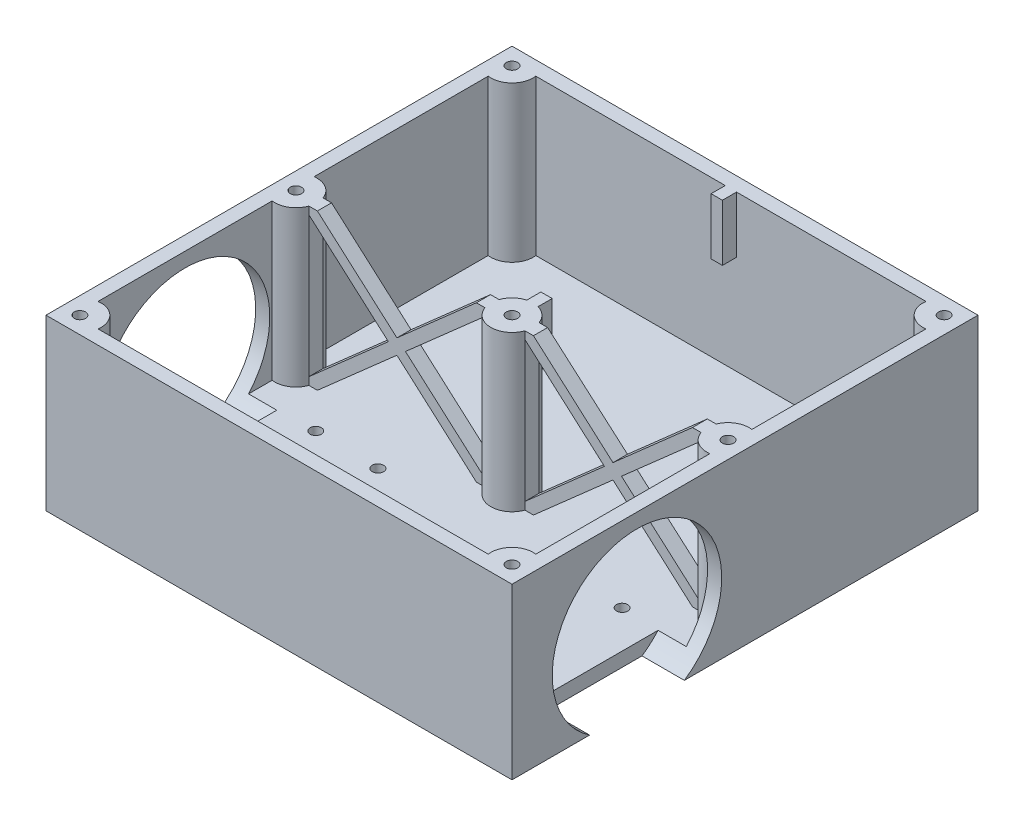
SolidWorks part; units mm, degrees
ref_plane "Plan de face" through (0, 0, 0) normal (0, 0, 1) x (1, 0, 0)
ref_plane "Plan de dessus" through (0, 0, 0) normal (0, 1, 0) x (1, 0, 0)
ref_plane "Plan de droite" through (0, 0, 0) normal (1, 0, 0) x (0, 0, -1)
sketch "Esquisse1" plane through (0, 0, 0) normal (0, 1, 0) x (1, 0, 0)
  line L0 (0, -92.04) -> (0, 96.9003) construction
  line L1 (82.5, 82.5) -> (-82.5, 82.5)
  line L2 (82.5, 82.5) -> (82.5, -82.5)
  line L3 (82.5, -82.5) -> (-82.5, -82.5)
  line L4 (-82.5, 82.5) -> (-82.5, -82.5)
  line L5 (82.5, 82.5) -> (-82.5, -82.5) construction
  line L6 (82.5, -82.5) -> (-82.5, 82.5) construction
  line L7 (69.067, -77.5) -> (-69.067, -77.5)
  line L8 (77.5, -69.067) -> (77.5, -7.433)
  line L9 (69.067, 77.5) -> (2, 77.5)
  line L10 (-77.5, -69.067) -> (-77.5, -7.433)
  line L11 (76.5, -76.5) -> (-76.5, 76.5) construction
  line L12 (76.5, 76.5) -> (-76.5, -76.5) construction
  line L13 (0, 0) -> (-103.5856, 0) construction
  line L14 (-77.5, 7.433) -> (-77.5, 69.067)
  line L15 (77.5, 7.433) -> (77.5, 69.067)
  line L16 (-69.4289, 2.5) -> (-7.0711, 2.5)
  line L17 (-69.4289, -2.5) -> (-7.0711, -2.5)
  line L18 (-2, 77.5) -> (-2, 7.2284)
  line L19 (7.0711, 2.5) -> (69.5275, 2.763)
  line L20 (7.0711, -2.5) -> (69.4289, -2.5)
  line L21 (2, 77.5) -> (2, 7.2284)
  line L22 (-2, 77.5) -> (-69.067, 77.5)
  line L23 (-76.5, -76.5) -> (-76.5, 76.5) construction
  arc A0 (-77.5, 69.067) -> (-69.067, 77.5) centre (-76.5, 76.5) ccw
  circle A1 centre (-76.5, 76.5) radius 2
  arc A2 (-77.5, -7.433) -> (-77.5, 7.433) centre (-76.5, 0) ccw
  circle A3 centre (-76.5, 0) radius 2
  circle A4 centre (-76.5, -76.5) radius 2
  arc A5 (-77.5, -69.067) -> (-69.067, -77.5) centre (-76.5, -76.5) cw
  circle A6 centre (76.5, 76.5) radius 2
  arc A7 (77.5, 69.067) -> (69.067, 77.5) centre (76.5, 76.5) cw
  arc A8 (77.5, -7.433) -> (77.5, 7.433) centre (76.5, 0) cw
  circle A9 centre (76.5, 0) radius 2
  circle A10 centre (76.5, -76.5) radius 2
  arc A11 (77.5, -69.067) -> (69.067, -77.5) centre (76.5, -76.5) ccw
  arc A12 (7.0711, 2.5) -> (2, 7.2284) centre (0, 0) ccw
  circle A13 centre (0, 0) radius 2
  arc A14 (-7.0711, -2.5) -> (7.0711, -2.5) centre (0, 0) ccw
  arc A15 (-2, 7.2284) -> (-7.0711, 2.5) centre (0, 0) ccw
  point P0 (0, 0)
  point P6 (0, 0)
  dimension "D3" = 15
  dimension "D6" = 4
  dimension "D8" = 4
  dimension "D9" = 2.5
  dimension "D10" = 15
  dimension "D11" = 4
  dimension "D15" = 7.5
  dimension "D1" = 165
  dimension "D2" = 165
  dimension "D4" = 5
  dimension "D5" = 5
  dimension "D7" = 2.5
  dimension "D12" = 2
  dimension "D13" = 2
  dimension "D14" = 6
extrude "BASE EXT" add sketch "Esquisse1" along normal blind 30 and the other way blind 25
sketch "Esquisse2" plane through (0, -25, 0) normal (0, -1, 0) x (1, 0, 0)
  line L0 (0, 93.4226) -> (0, -99.355) construction
  line L1 (82.5, 82.5) -> (-82.5, 82.5)
  line L2 (82.5, 82.5) -> (82.5, -82.5)
  line L3 (82.5, -82.5) -> (-82.5, -82.5)
  line L4 (-82.5, 82.5) -> (-82.5, -82.5)
  line L5 (82.5, 82.5) -> (-82.5, -82.5) construction
  line L6 (82.5, -82.5) -> (-82.5, 82.5) construction
  circle A35 centre (-76.5, 0) radius 5
  circle A36 centre (-76.5, -76.5) radius 5
  circle A37 centre (76.5, -76.5) radius 5
  circle A38 centre (76.5, 0) radius 5
  circle A39 centre (76.5, 76.5) radius 5
  circle A40 centre (0, 0) radius 5
  circle A42 centre (-76.5, 76.5) radius 5
  point P0 (0, 0)
  dimension "D1" = 10
  dimension "D2" = 10
  dimension "D3" = 10
  dimension "D4" = 10
extrude "BASE BAS" add sketch "Esquisse2" along normal blind 5
sketch "Esquisse4" plane through (-77.5, 0, 0) normal (1, 0, 0) x (0, 0, -1)
  line L1 (-69.067, -25) -> (-7.433, -25) construction
  line L2 (-38.25, -25) -> (-38.25, 16.399) construction
  circle A0 centre (-38.25, -5.1286) radius 30
  point P0 (-38.25, -25)
  point P7 (-38.25, 24.8714)
  dimension "D1" = 60
extrude "ACCES ROUES" cut sketch "Esquisse4" against normal blind 6 and the other way blind 10
mirror "SYM ACCES ROUE" about plane through (0, 0, 0) normal (1, 0, 0) of "ACCES ROUES"
sketch "Esquisse7" plane through (0, -25, 0) normal (0, 1, 0) x (1, 0, 0)
  line L0 (-54.2324, -15.25) -> (-54.2324, -61.25) construction
  line L1 (-54.2324, -61.25) -> (-31.7324, -60.75) construction
  line L2 (-31.7324, -60.75) -> (-31.7324, -15.75) construction
  line L3 (-31.7324, -15.75) -> (-54.2324, -15.25) construction
  line L4 (-54.2324, -15.25) -> (-31.7324, -60.75) construction
  line L5 (-31.7324, -60.75) -> (-54.2324, -61.25) construction
  line L6 (-54.2324, -61.25) -> (-31.7324, -15.75) construction
  line L7 (0, 0) -> (-76.5, -76.5) construction
  line L8 (-38.25, -38.25) -> (-73.5574, -38.25) construction
  line L9 (-42.8587, -38.25) -> (-69.3083, -38.25) construction
  line L10 (0, 0) -> (0, -89.1386) construction
  line L11 (54.2324, -61.25) -> (31.7324, -15.75) construction
  line L12 (31.7324, -60.75) -> (54.2324, -61.25) construction
  line L13 (54.2324, -15.25) -> (31.7324, -60.75) construction
  line L14 (31.7324, -15.75) -> (54.2324, -15.25) construction
  line L15 (31.7324, -60.75) -> (31.7324, -15.75) construction
  line L16 (54.2324, -61.25) -> (31.7324, -60.75) construction
  line L17 (54.2324, -15.25) -> (54.2324, -61.25) construction
  circle A0 centre (54.2324, -61.25) radius 2
  circle A1 centre (31.7324, -60.75) radius 2
  circle A2 centre (31.7324, -15.75) radius 2
  circle A3 centre (54.2324, -15.25) radius 2
  circle A4 centre (-54.2324, -15.25) radius 2
  circle A5 centre (-31.7324, -15.75) radius 2
  circle A6 centre (-31.7324, -60.75) radius 2
  circle A7 centre (-54.2324, -61.25) radius 2
  point P2 (-42.8587, -38.25)
  point P26 (42.8587, -38.25)
  dimension "D2" = 4
  dimension "D3" = 4
  dimension "D4" = 4
  dimension "D5" = 4
  dimension "D1" = 0
extrude "VIDE SUPPORT MOTEUR" cut sketch "Esquisse7" against normal up to surface (5 mm away) up to face at (0, -30, -5)
sketch "Esquisse9" plane through (0, -30, 0) normal (0, -1, 0) x (1, 0, 0)
  line L0 (0, 0) -> (0, 70.4608) construction
  circle A0 centre (-54.2324, 61.25) radius 5
  circle A1 centre (-31.7324, 60.75) radius 5
  circle A2 centre (-54.2324, 15.25) radius 5
  circle A3 centre (-31.7324, 15.75) radius 5
  circle A4 centre (31.7324, 15.75) radius 5
  circle A5 centre (54.2324, 15.25) radius 5
  circle A6 centre (31.7324, 60.75) radius 5
  circle A7 centre (54.2324, 61.25) radius 5
  dimension "D1" = 10
  dimension "D2" = 10
  dimension "D3" = 10
  dimension "D4" = 10
extrude "VIS MOTEUR 10mm" cut sketch "Esquisse9" against normal blind 2
sketch "Esquisse10" plane through (0, -30, 0) normal (0, -1, 0) x (1, 0, 0)
  line L0 (-82.5, 21.4746) -> (-82.5, -82.5) construction
  line L1 (-82.5, -82.5) -> (82.5, -82.5) construction
  line L2 (82.5, -82.5) -> (82.5, 21.4746) construction
  circle A0 centre (-42.5, -52.5) radius 2
  circle A1 centre (42.5, -52.5) radius 2
  point P0 (-42.5, -52.5)
  point P1 (42.5, -52.5)
  dimension "D5" = 4
  dimension "D6" = 4
  dimension "D1" = 40
  dimension "D2" = 30
  dimension "D3" = 30
  dimension "D4" = 40
extrude "VIS PATIN" cut sketch "Esquisse10" against normal up to surface (5 mm away) up to face at (43.1933, -25, -34.8428)
sketch "Esquisse11" plane through (0, 0, 2.5) normal (0, 0, 1) x (1, 0, 0)
  line L0 (-69.4289, 30) -> (-7.0711, -25) construction
  line L1 (-7.0711, -25) -> (-7.0711, 30) construction
  line L2 (-7.0711, 30) -> (-69.4289, -25) construction
  line L3 (-38.25, 30) -> (-38.25, -25) construction
  line L4 (-69.4289, 27.3332) -> (-41.2735, 2.5)
  line L5 (-69.4289, 30) -> (-7.0711, 30) construction
  line L6 (-69.4289, -25) -> (-7.0711, -25) construction
  line L7 (-7.0711, 2.5) -> (-69.4289, 2.5) construction
  line L8 (-69.4289, -25) -> (-69.4289, 30) construction
  line L9 (-66.4054, 30) -> (-38.25, 5.1668)
  line L10 (-38.25, 5.1668) -> (-10.0946, 30)
  line L11 (-10.0946, 30) -> (-66.4054, 30)
  line L12 (-41.2735, 2.5) -> (-69.4289, -22.3332)
  line L13 (-69.4289, -22.3332) -> (-69.4289, 27.3332)
  line L14 (-7.0711, -22.3332) -> (-7.0711, 27.3332)
  line L15 (-35.2265, 2.5) -> (-7.0711, -22.3332)
  line L16 (-7.0711, 27.3332) -> (-35.2265, 2.5)
  line L17 (-10.0946, -25) -> (-66.4054, -25)
  line L18 (-38.25, -0.1668) -> (-10.0946, -25)
  line L19 (-66.4054, -25) -> (-38.25, -0.1668)
  line L20 (0, 30) -> (0, -25) construction
  line L21 (7.0711, 2.5) -> (69.4289, 2.5) construction
  line L22 (38.25, 30) -> (38.25, -25) construction
  line L23 (7.0711, 30) -> (69.4289, -25) construction
  line L24 (7.0711, -25) -> (7.0711, 30) construction
  line L25 (69.4289, 30) -> (7.0711, -25) construction
  line L26 (66.4054, -25) -> (38.25, -0.1668)
  line L27 (38.25, -0.1668) -> (10.0946, -25)
  line L28 (10.0946, -25) -> (66.4054, -25)
  line L29 (7.0711, 27.3332) -> (35.2265, 2.5)
  line L30 (35.2265, 2.5) -> (7.0711, -22.3332)
  line L31 (7.0711, -22.3332) -> (7.0711, 27.3332)
  line L32 (69.4289, -22.3332) -> (69.4289, 27.3332)
  line L33 (41.2735, 2.5) -> (69.4289, -22.3332)
  line L34 (10.0946, 30) -> (66.4054, 30)
  line L35 (38.25, 5.1668) -> (10.0946, 30)
  line L36 (66.4054, 30) -> (38.25, 5.1668)
  line L37 (69.4289, 27.3332) -> (41.2735, 2.5)
  dimension "D1" = 2
  dimension "D2" = 2
extrude "VIDE CROIX" cut sketch "Esquisse11" against normal blind 11
sketch "Esquisse12" plane through (-2, 0, 0) normal (-1, 0, 0) x (0, 0, 1)
  line L1 (-77.5, -25) -> (-7.2284, -25) construction
  line L2 (-7.2284, 10) -> (-12.2284, 10)
  line L3 (-12.2284, 10) -> (-12.2284, 30)
  line L4 (-12.2284, 30) -> (-72.5, 30)
  line L5 (-42.3642, -25) -> (-42.3642, 58.0428) construction
  line L6 (-77.5, 10) -> (-72.5, 10)
  line L7 (-7.2284, 10) -> (-7.2284, -25)
  line L8 (-7.2284, -25) -> (-77.5, -25)
  line L9 (-72.5, 10) -> (-72.5, 30)
  line L10 (-77.5, 30) -> (-7.2284, 30) construction
  line L12 (-77.5, 10) -> (-77.5, -25)
  dimension "D1" = 20
  dimension "D2" = 5
extrude "VIDE GUIDAGE" cut sketch "Esquisse12" against normal up to surface (4 mm away) up to face at (2, 2.5, -42.3642)
